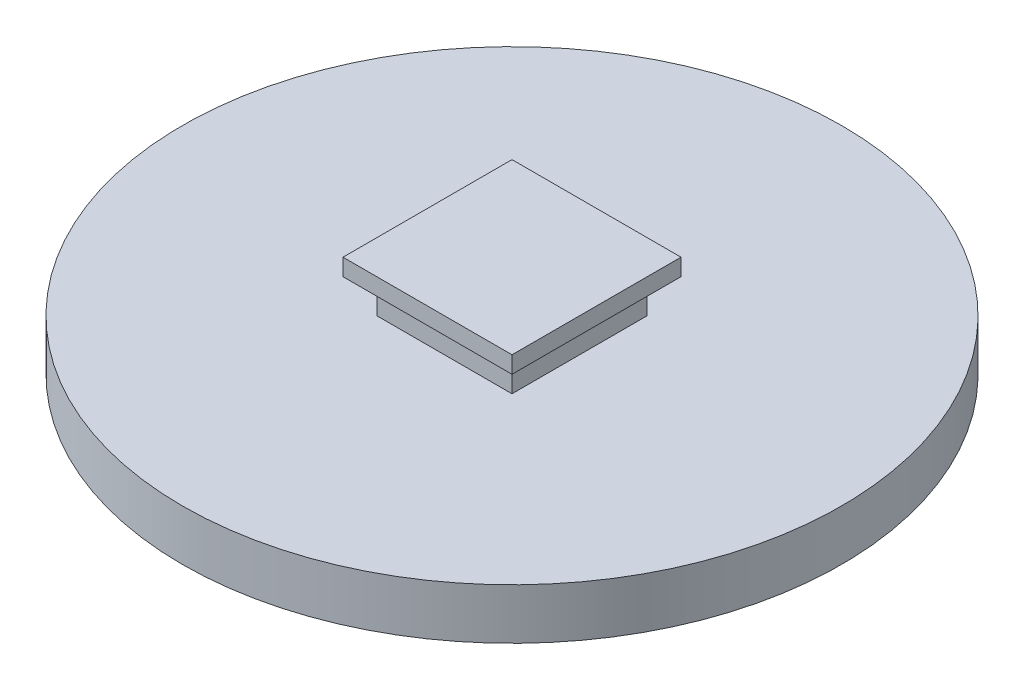
SolidWorks part; units mm, degrees
ref_plane "Front Plane" through (0, 0, 0) normal (0, 0, 1) x (1, 0, 0)
ref_plane "Top Plane" through (0, 0, 0) normal (0, 1, 0) x (1, 0, 0)
ref_plane "Right Plane" through (0, 0, 0) normal (1, 0, 0) x (0, 0, -1)
sketch "Sketch1" plane through (0, 0, 0) normal (0, 1, 0) x (1, 0, 0)
  circle A0 centre (0, 0) radius 49.53
  dimension "D1" = 99.06
extrude "Boss-Extrude1" add sketch "Sketch1" along normal blind 7.62
sketch "Sketch2" plane through (0, 0, 0) normal (0, -1, 0) x (1, 0, 0)
  line L0 (0, -49.53) -> (0, 49.53) construction
  line L1 (49.53, 0) -> (-49.53, 0) construction
  circle A2 centre (0, 0) radius 49.53 construction
  circle A3 centre (-48.26, 0) radius 0.889
  point P6 (0, 0)
  point P9 (0, 0)
  dimension "D1" = 1.778
  dimension "D2" = 1.27
extrude "Cut-Extrude1" cut sketch "Sketch2" against normal blind 2.54
pattern_circular "CirPattern1" count 8 over 360 about axis through (0, 0, 0) along (0, 1, 0) of "Cut-Extrude1"
sketch "Sketch4" plane through (0, 0, 0) normal (0, -1, 0) x (1, 0, 0)
  line L0 (49.53, 0) -> (-49.53, 0) construction
  line L1 (0, -49.53) -> (0, 49.53) construction
  line L3 (2.5273, 25.273) -> (-2.5273, 25.273)
  line L4 (2.5273, 25.273) -> (2.5273, -25.273)
  line L5 (2.5273, -25.273) -> (-2.5273, -25.273)
  line L6 (-2.5273, 25.273) -> (-2.5273, -25.273)
  line L7 (2.5273, 25.273) -> (-2.5273, -25.273) construction
  line L8 (2.5273, -25.273) -> (-2.5273, 25.273) construction
  circle A0 centre (0, 0) radius 49.53 construction
  point P0 (0, 0)
  point P6 (0, 0)
  point P11 (0, 0)
  dimension "D1" = 5.0546
  dimension "D2" = 50.546
extrude "Boss-Extrude3" add sketch "Sketch4" along normal blind 2.54
sketch "Sketch5" plane through (0, 7.62, 0) normal (0, 1, 0) x (1, 0, 0)
  line L1 (10.16, 10.16) -> (-10.16, 10.16)
  line L2 (10.16, 10.16) -> (10.16, -10.16)
  line L3 (10.16, -10.16) -> (-10.16, -10.16)
  line L4 (-10.16, 10.16) -> (-10.16, -10.16)
  line L5 (10.16, 10.16) -> (-10.16, -10.16) construction
  line L6 (10.16, -10.16) -> (-10.16, 10.16) construction
  point P0 (0, 0)
  dimension "D1" = 20.32
  dimension "D2" = 20.32
extrude "Boss-Extrude4" add sketch "Sketch5" along normal blind 5.08
sketch "Sketch6" plane through (0, 12.7, 0) normal (0, 1, 0) x (1, 0, 0)
  line L1 (12.7, 12.7) -> (-12.7, 12.7)
  line L2 (12.7, 12.7) -> (12.7, -12.7)
  line L3 (12.7, -12.7) -> (-12.7, -12.7)
  line L4 (-12.7, 12.7) -> (-12.7, -12.7)
  line L5 (12.7, 12.7) -> (-12.7, -12.7) construction
  line L6 (12.7, -12.7) -> (-12.7, 12.7) construction
  point P0 (0, 0)
  dimension "D1" = 25.4
  dimension "D2" = 25.4
extrude "Boss-Extrude5" add sketch "Sketch6" along normal blind 2.54
